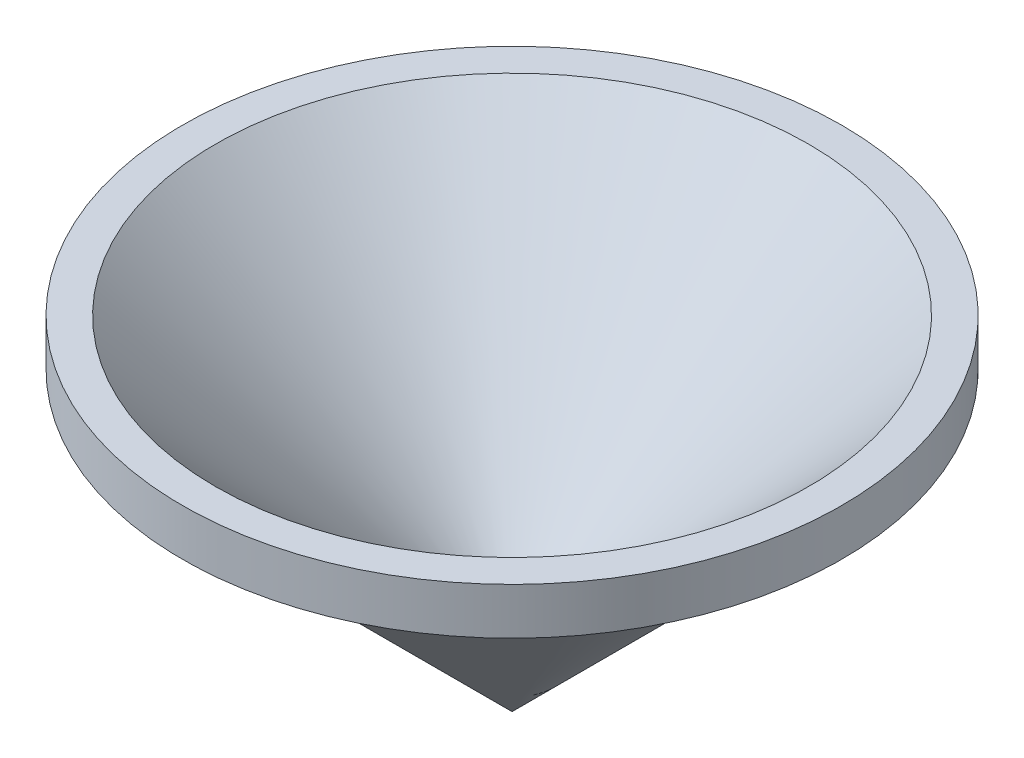
SolidWorks part; units mm, degrees
ref_plane "Front Plane" through (0, 0, 0) normal (0, 0, 1) x (1, 0, 0)
ref_plane "Top Plane" through (0, 0, 0) normal (0, 1, 0) x (1, 0, 0)
ref_plane "Right Plane" through (0, 0, 0) normal (1, 0, 0) x (0, 0, -1)
sketch "Sketch1" plane through (0, 0, 0) normal (0, 0, 1) x (1, 0, 0)
  line L0 (0, 0) -> (0, 14.7439) construction
  line L1 (18, 0) -> (18, 24.5732) construction
  line L2 (0, 0) -> (18, 18)
  line L3 (18, 18) -> (20, 18)
  line L4 (20, 18) -> (20, 20.8284)
  line L5 (20, 20.8284) -> (18, 20.8284)
  line L6 (18, 20.8284) -> (0, 2.8284)
  line L7 (0, 0) -> (0, 2.8284)
  point P3 (18, 0)
  dimension "D1" = 18
  dimension "D2" = 2
  dimension "D3" = 2
revolve "Revolve1" add sketch "Sketch1" angle 360 about L0
